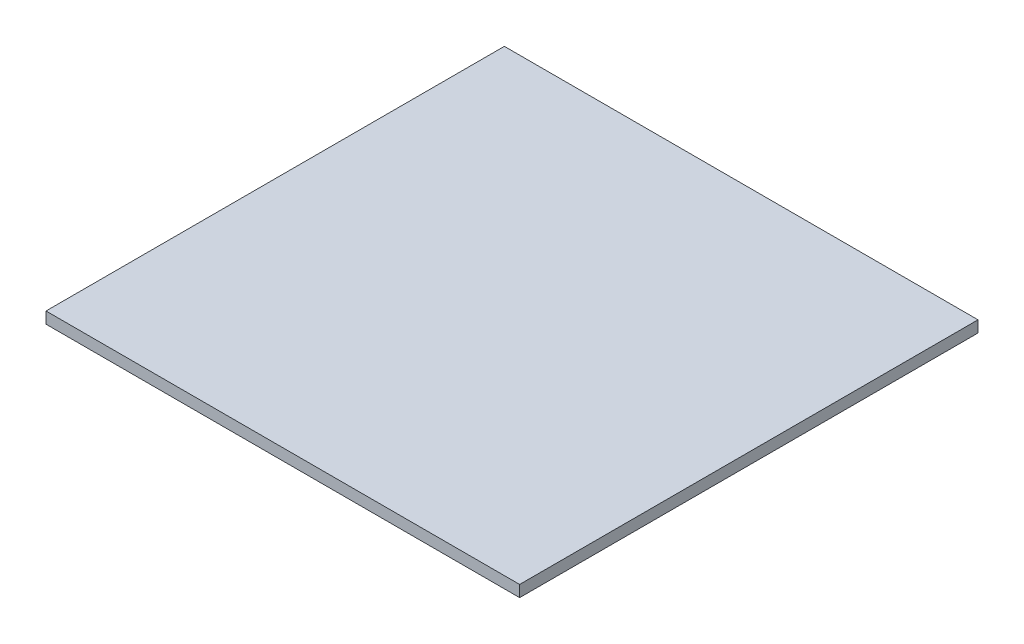
SolidWorks part; units mm, degrees
material "Balsa"
ref_plane "Plano frontal" through (0, 0, 0) normal (0, 0, 1) x (1, 0, 0)
ref_plane "Plano superior" through (0, 0, 0) normal (0, 1, 0) x (1, 0, 0)
ref_plane "Plano direito" through (0, 0, 0) normal (1, 0, 0) x (0, 0, -1)
sketch "Esboço1" plane through (0, 0, 0) normal (0, 1, 0) x (1, 0, 0)
  line L1 (-300, -300) -> (300, -300)
  line L2 (-300, -300) -> (-300, 300)
  line L3 (-300, 300) -> (300, 300)
  line L4 (300, -300) -> (300, 300)
  line L5 (-300, -300) -> (300, 300) construction
  line L6 (-300, 300) -> (300, -300) construction
  point P0 (0, 0)
  dimension "D1" = 600
  dimension "D2" = 600
extrude "Ressalto-extrusão1" add sketch "Esboço1" along normal blind 15
ref_plane "Plane1" through (0, 0, 0) normal (0, 0, 1) x (1, 0, 0)
sketch "Sketch1" plane through (300, 0, 0) normal (1, 0, 0) x (0, 0, -1)
  line L1 (-300, 0) -> (300, 0)
  line L2 (-300, 0) -> (-300, 15)
  line L3 (-300, 15) -> (300, 15)
  line L4 (300, 0) -> (300, 15)
extrude "Boss-Extrude1" add sketch "Sketch1" along normal blind 20
